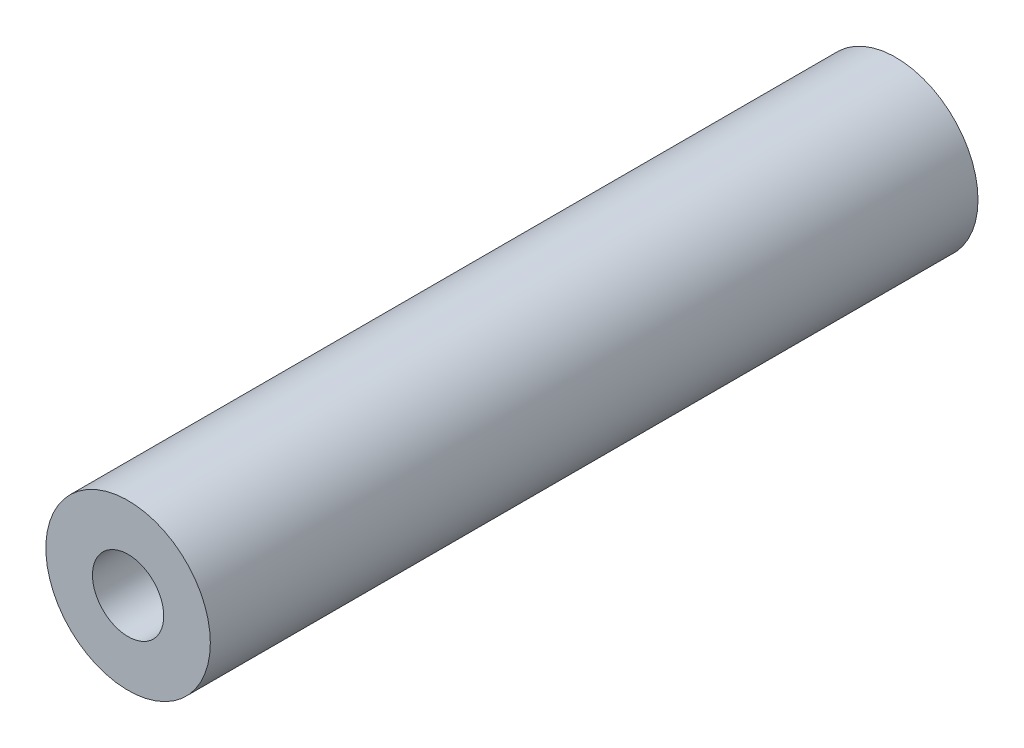
SolidWorks part; units mm, degrees
ref_plane "前视基准面" through (0, 0, 0) normal (0, 0, 1) x (1, 0, 0)
ref_plane "上视基准面" through (0, 0, 0) normal (0, 1, 0) x (1, 0, 0)
ref_plane "右视基准面" through (0, 0, 0) normal (1, 0, 0) x (0, 0, -1)
other "Configuration Table"
sketch "Spacer_OD6_ID2p6" plane through (0, 0, 0) normal (0, 0, 1) x (1, 0, 0)
  circle A0 centre (0, 0) radius 3
  circle A1 centre (0, 0) radius 1.3
extrude "Rear_gap_28mm" add sketch "Spacer_OD6_ID2p6" along normal blind 28
